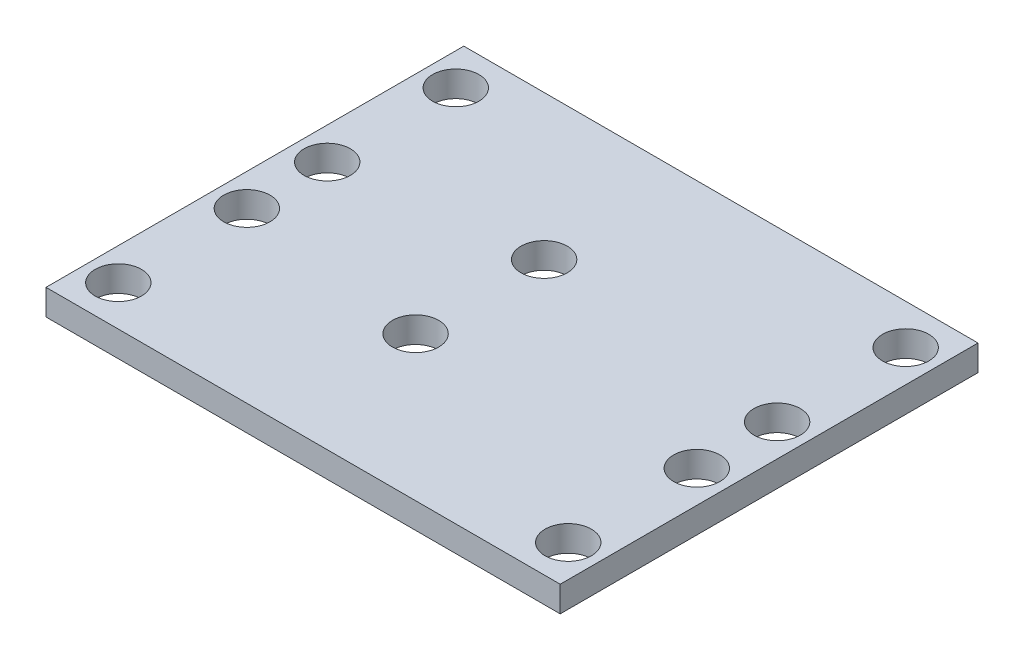
SolidWorks part; units mm, degrees
ref_plane "Front Plane" through (0, 0, 0) normal (0, 0, 1) x (1, 0, 0)
ref_plane "Top Plane" through (0, 0, 0) normal (0, 1, 0) x (1, 0, 0)
ref_plane "Right Plane" through (0, 0, 0) normal (1, 0, 0) x (0, 0, -1)
sketch "Sketch1" plane through (0, 0, 0) normal (0, 1, 0) x (1, 0, 0)
  line L0 (-25.4, -14.2875) -> (-25.4, -26.9875)
  line L1 (-22.225, -10.3187) -> (22.225, -10.3187) construction
  line L2 (-22.225, -10.3187) -> (-22.225, 10.3187) construction
  line L3 (-22.225, 10.3187) -> (22.225, 10.3187) construction
  line L4 (22.225, -10.3187) -> (22.225, 10.3187) construction
  line L5 (-22.225, -10.3187) -> (22.225, 10.3187) construction
  line L6 (-22.225, 10.3187) -> (22.225, -10.3187) construction
  line L7 (-25.4, -14.2875) -> (25.4, -14.2875) construction
  line L8 (-25.4, -14.2875) -> (-25.4, 14.2875)
  line L9 (-25.4, 14.2875) -> (25.4, 14.2875)
  line L10 (25.4, -14.2875) -> (25.4, 14.2875)
  line L11 (-25.4, -14.2875) -> (25.4, 14.2875) construction
  line L12 (-25.4, 14.2875) -> (25.4, -14.2875) construction
  line L13 (-25.4, -26.9875) -> (25.4, -26.9875)
  line L14 (25.4, -14.2875) -> (25.4, -26.9875)
  circle A0 centre (-22.225, 10.3187) radius 2.286
  circle A1 centre (-22.225, -10.3187) radius 2.286
  circle A2 centre (22.225, -10.3187) radius 2.286
  circle A3 centre (22.225, 10.3187) radius 2.286
  circle A5 centre (-22.225, -2.3812) radius 2.286
  circle A6 centre (-22.225, -23.0187) radius 2.286
  circle A8 centre (22.225, -23.0187) radius 2.286
  circle A9 centre (22.225, -2.3812) radius 2.286
  circle A10 centre (-3.175, 0) radius 2.286
  circle A11 centre (-3.175, -12.7) radius 2.286
  point P0 (0, 0)
  point P6 (0, 0)
  dimension "D5" = 4.572
  dimension "D1" = 44.45
  dimension "D2" = 20.6375
  dimension "D3" = 50.8
  dimension "D4" = 28.575
  dimension "D6" = 12.7
  dimension "D8" = 3.175
  dimension "D7" = 2
extrude "Boss-Extrude1" add sketch "Sketch1" along normal blind 2.54
